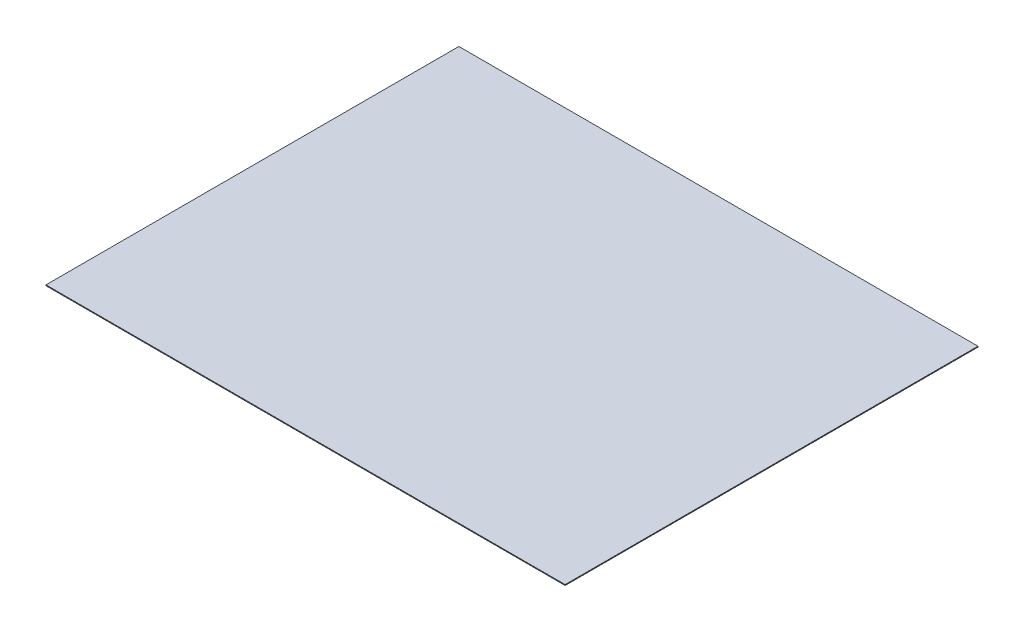
SolidWorks part; units mm, degrees
ref_plane "Front" through (0, 0, 0) normal (0, 0, 1) x (1, 0, 0)
ref_plane "Top" through (0, 0, 0) normal (0, 1, 0) x (1, 0, 0)
ref_plane "Right" through (0, 0, 0) normal (1, 0, 0) x (0, 0, -1)
sketch "Эскиз1" plane through (0, 0, 0) normal (0, 1, 0) x (1, 0, 0)
  line L1 (0, 0) -> (127, 0)
  line L2 (0, 0) -> (0, -101)
  line L3 (0, -101) -> (127, -101)
  line L4 (127, 0) -> (127, -101)
  dimension "D1" = 101
  dimension "D2" = 127
extrude "Бобышка-Вытянуть1" add sketch "Эскиз1" along normal blind 0.2
